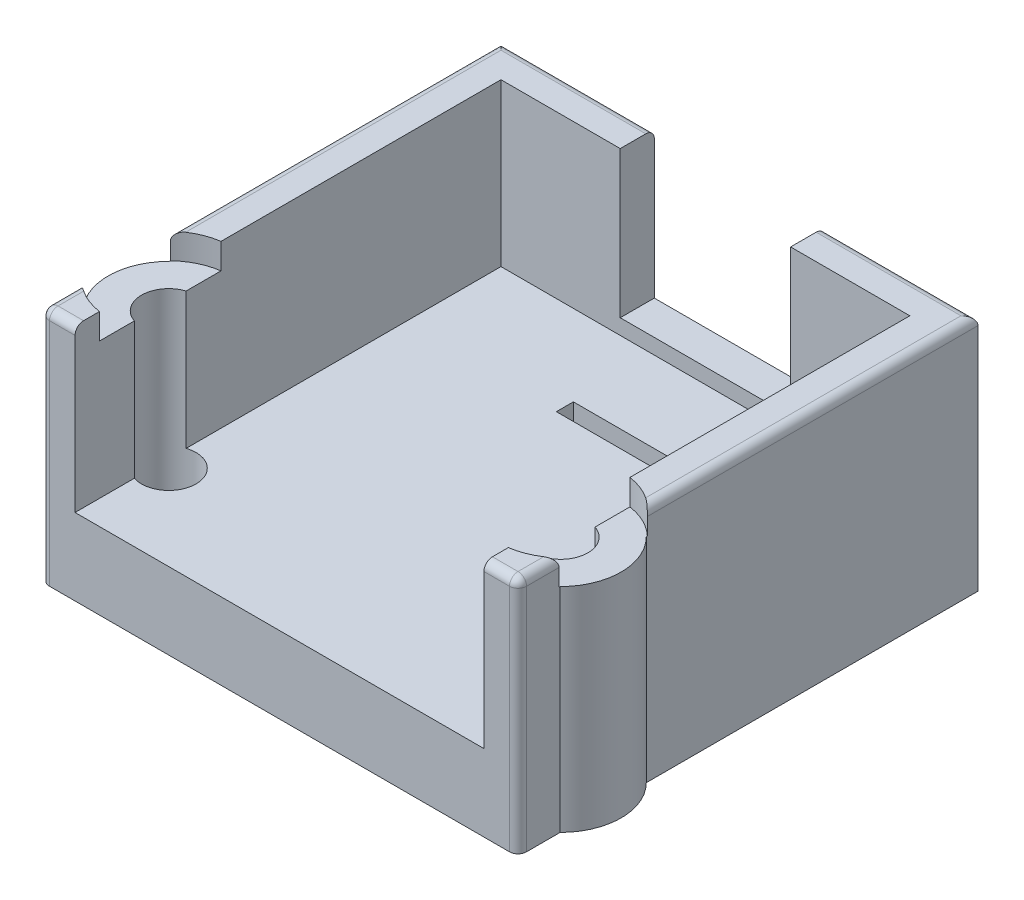
SolidWorks part; units mm, degrees
ref_plane "Front Plane" through (0, 0, 0) normal (0, 0, 1) x (1, 0, 0)
ref_plane "Top Plane" through (0, 0, 0) normal (0, 1, 0) x (1, 0, 0)
ref_plane "Right Plane" through (0, 0, 0) normal (1, 0, 0) x (0, 0, -1)
sketch "Sketch1" plane through (0, 0, 0) normal (0, 1, 0) x (1, 0, 0)
  line L1 (-14, -13.5) -> (14, -13.5)
  line L2 (-14, -13.5) -> (-14, 13.5)
  line L3 (-14, 13.5) -> (14, 13.5)
  line L4 (14, -13.5) -> (14, 13.5)
  line L5 (-14, -13.5) -> (14, 13.5) construction
  line L6 (-14, 13.5) -> (14, -13.5) construction
  point P0 (0, 0)
  point P5 (0, 0)
  dimension "D1" = 27
  dimension "D2" = 28
extrude "Boss-Extrude1" add sketch "Sketch1" along normal blind 14 contours L3 L4 L1 L2
shell "Shell1" thickness 2
sketch "Sketch2" plane through (0, 2, 0) normal (0, 1, 0) x (1, 0, 0)
  line L1 (-12, -11.5) -> (12, -11.5)
  line L2 (-12, -11.5) -> (-12, 11.5)
  line L3 (-12, 11.5) -> (12, 11.5)
  line L4 (12, -11.5) -> (12, 11.5)
  line L5 (-12, -11.5) -> (12, 11.5) construction
  line L6 (-12, 11.5) -> (12, -11.5) construction
  line L7 (-3, 5.75) -> (3, 5.75)
  line L8 (-3, 5.75) -> (-3, 6.75)
  line L9 (-3, 6.75) -> (3, 6.75)
  line L10 (3, 5.75) -> (3, 6.75)
  line L11 (-3, 5.75) -> (3, 6.75) construction
  line L12 (-3, 6.75) -> (3, 5.75) construction
  point P0 (0, 0)
  point P5 (0, 6.25)
  point P12 (0, 0)
  dimension "D1" = 4.75
  dimension "D2" = 1
  dimension "D3" = 6
extrude "Boss-Extrude2" add sketch "Sketch2" along normal blind 2.5
sketch "Sketch3" plane through (0, 0, 13.5) normal (0, 0, 1) x (1, 0, 0)
  line L0 (-14, 14) -> (14, 14) construction
  line L1 (-12, 14) -> (12, 14)
  line L2 (-12, 14) -> (-12, 4.5)
  line L3 (-12, 4.5) -> (12, 4.5)
  line L4 (12, 14) -> (12, 4.5)
  line L5 (-12, 14) -> (12, 4.5) construction
  line L6 (-12, 4.5) -> (12, 14) construction
  line L7 (-12, 4.5) -> (12, 4.5) construction
  point P0 (0, 9.25)
  point P5 (0, 0)
  point P6 (0, 0)
  point P9 (0, 0)
  point P12 (0, 0)
  point P14 (0, 0)
extrude "Cut-Extrude1" cut sketch "Sketch3" against normal up to next
sketch "Sketch4" plane through (0, 14, 0) normal (0, 1, 0) x (1, 0, 0)
  line L0 (-11.5, -8.5) -> (11.5, -8.5) construction
  line L1 (0, -8.5) -> (0, -13.5) construction
  line L2 (-12, -13.5) -> (12, -13.5) construction
  circle A0 centre (-11.5, -8.5) radius 1.6
  circle A1 centre (11.5, -8.5) radius 1.6
  point P10 (0, 0)
  point P11 (0, 0)
  dimension "D1" = 5
  dimension "D3" = 3.2
  dimension "D2" = 23
extrude "Cut-Extrude2" cut sketch "Sketch4" against normal up to next
sketch "Sketch5" plane through (0, 14, 0) normal (0, 1, 0) x (1, 0, 0)
  line L10 (12, -6.9801) -> (12, 11.5) construction
  line L11 (12, -13.5) -> (12, -10.0199) construction
  line L12 (12, -4.9801) -> (12, -6.9801)
  line L13 (12, -10.0199) -> (12, -12.0199)
  line L14 (0, -7.7) -> (0, 7.7) construction
  line L15 (-12, -4.9801) -> (-12, -6.9801)
  line L16 (-12, -10.0199) -> (-12, -12.0199)
  arc A9 (12, -10.0199) -> (12, -6.9801) centre (11.5, -8.5) ccw
  arc A10 (12, -4.9801) -> (12, -12.0199) centre (11.5, -8.5) cw
  arc A11 (12, -10.0199) -> (12, -6.9801) centre (11.5, -8.5) ccw construction
  arc A12 (-12, -10.0199) -> (-12, -6.9801) centre (-11.5, -8.5) cw
  arc A13 (-12, -4.9801) -> (-12, -12.0199) centre (-11.5, -8.5) ccw
  dimension "D1" = 2
extrude "Boss-Extrude3" add sketch "Sketch5" against normal up to surface (14 mm away) up to face at (-11.5, 0, 6.9)
sketch "Sketch7" plane through (0, 0, -11.5) normal (0, 0, 1) x (1, 0, 0)
  line L0 (-12, 14) -> (12, 14) construction
  line L1 (-5, 5.4) -> (5, 5.4)
  line L2 (-5, 5.4) -> (-5, 14)
  line L3 (-5, 14) -> (5, 14)
  line L4 (5, 5.4) -> (5, 14)
  line L5 (-5, 5.4) -> (5, 14) construction
  line L6 (-5, 14) -> (5, 5.4) construction
  line L7 (14, 0) -> (14, 14) construction
  point P0 (0, 9.7)
  point P5 (0, 0)
  point P8 (0, 0)
  dimension "D1" = 8.6
  dimension "D2" = 9
extrude "Cut-Extrude4" cut sketch "Sketch7" against normal up to next
sketch "Sketch8" plane through (0, 14, 0) normal (0, 1, 0) x (1, 0, 0)
  circle A0 centre (11.5, -8.5) radius 3.6
  circle A1 centre (-11.5, -8.5) radius 3.6
  arc A2 (-12, -10.0199) -> (-12, -6.9801) centre (-11.5, -8.5) ccw construction
  arc A3 (12, -6.9801) -> (12, -10.0199) centre (11.5, -8.5) ccw construction
  dimension "D1" = 7.2
extrude "Cut-Extrude5" cut sketch "Sketch8" against normal blind 1.5
fillet "Fillet1" radius 0.5 10 edges at (-14, 7, 13.5) (14, 7, 13.5) (-14, 14, 12.2952) (-13, 14, 13.5) (-14, 14, -3.7952) (-9.5, 14, -13.5) (9.5, 14, -13.5) (14, 14, -3.7952) (14, 14, 12.2952) (13, 14, 13.5)
